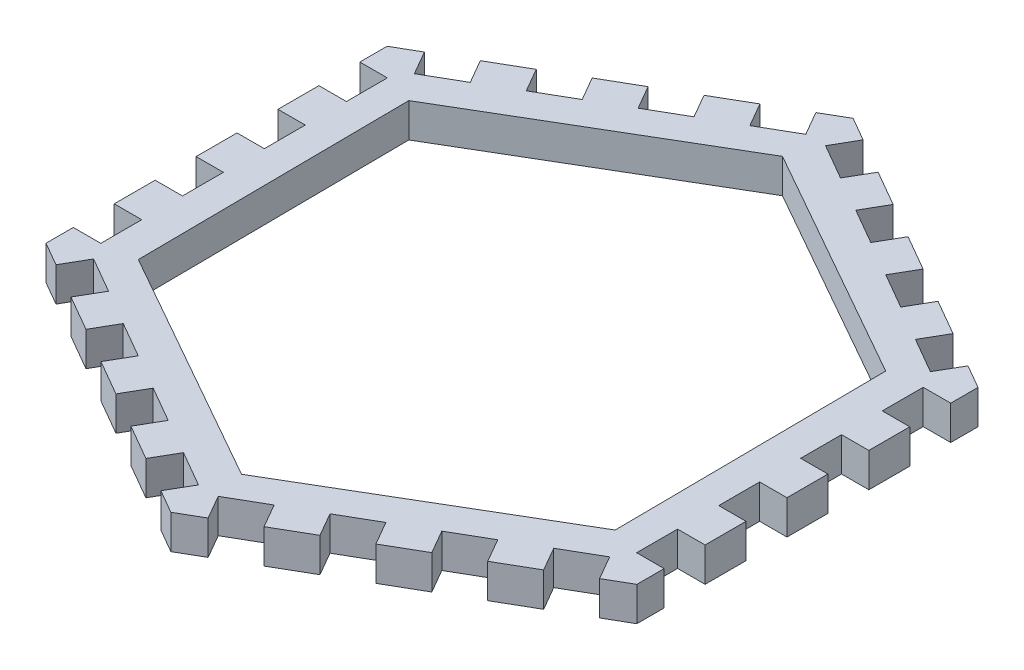
SolidWorks part; units mm, degrees
ref_plane "Front Plane" through (0, 0, 0) normal (0, 0, 1) x (1, 0, 0)
ref_plane "Top Plane" through (0, 0, 0) normal (0, 1, 0) x (1, 0, 0)
ref_plane "Right Plane" through (0, 0, 0) normal (1, 0, 0) x (0, 0, -1)
sketch "Sketch1" plane through (0, 0, 0) normal (0, 1, 0) x (1, 0, 0)
  line L0 (-13.7482, 23.8125) -> (-10.2854, 17.8149) construction
  line L1 (27.4963, 15.875) -> (0, 31.75) construction
  line L2 (0, 31.75) -> (-27.4963, 15.875) construction
  line L3 (-27.4963, 15.875) -> (-27.4963, -15.875) construction
  line L4 (-27.4963, -15.875) -> (0, -31.75) construction
  line L5 (0, -31.75) -> (27.4963, -15.875) construction
  line L6 (27.4963, -15.875) -> (27.4963, 15.875) construction
  line L7 (21.8831, 12.8954) -> (-0.2262, 25.399)
  line L8 (-0.2262, 25.399) -> (-22.1093, 12.5036)
  line L9 (-22.1093, 12.5036) -> (-21.8831, -12.8954)
  line L10 (-21.8831, -12.8954) -> (0.2262, -25.399)
  line L11 (0.2262, -25.399) -> (22.1093, -12.5036)
  line L12 (22.1093, -12.5036) -> (21.8831, 12.8954)
  line L13 (-27.4963, 15.875) -> (-25.2966, 17.145)
  line L14 (-25.2966, 17.145) -> (-24.0164, 14.9276)
  line L15 (-24.0164, 14.9276) -> (-20.7168, 16.8326)
  line L16 (-20.7168, 16.8326) -> (-21.997, 19.05)
  line L17 (-21.997, 19.05) -> (-18.6975, 20.955)
  line L18 (-18.6975, 20.955) -> (-17.4275, 18.7553)
  line L19 (-17.4275, 18.7553) -> (-14.1279, 20.6603)
  line L20 (-14.1279, 20.6603) -> (-15.3979, 22.86)
  line L21 (-15.3979, 22.86) -> (-12.0984, 24.765)
  line L22 (-10.8284, 22.5653) -> (-12.0984, 24.765)
  line L23 (-7.5288, 24.4703) -> (-10.8284, 22.5653)
  line L24 (-8.7988, 26.67) -> (-7.5288, 24.4703)
  line L25 (-5.4993, 28.575) -> (-8.7988, 26.67)
  line L26 (-4.2191, 26.3576) -> (-5.4993, 28.575)
  line L27 (-0.9195, 28.2626) -> (-4.2191, 26.3576)
  line L28 (-2.1997, 30.48) -> (-0.9195, 28.2626)
  line L29 (0, 31.75) -> (-2.1997, 30.48)
  line L30 (0, 31.75) -> (2.1997, 30.48)
  line L31 (2.1997, 30.48) -> (0.9195, 28.2626)
  line L32 (0.9195, 28.2626) -> (4.2191, 26.3576)
  line L33 (4.2191, 26.3576) -> (5.4993, 28.575)
  line L34 (5.4993, 28.575) -> (8.7988, 26.67)
  line L35 (8.7988, 26.67) -> (7.5288, 24.4703)
  line L36 (7.5288, 24.4703) -> (10.8284, 22.5653)
  line L37 (10.8284, 22.5653) -> (12.0984, 24.765)
  line L38 (12.0984, 24.765) -> (15.3979, 22.86)
  line L39 (14.1279, 20.6603) -> (15.3979, 22.86)
  line L40 (17.4275, 18.7553) -> (14.1279, 20.6603)
  line L41 (18.6975, 20.955) -> (17.4275, 18.7553)
  line L42 (21.997, 19.05) -> (18.6975, 20.955)
  line L43 (20.7168, 16.8326) -> (21.997, 19.05)
  line L44 (24.0164, 14.9276) -> (20.7168, 16.8326)
  line L45 (25.2966, 17.145) -> (24.0164, 14.9276)
  line L46 (27.4963, 15.875) -> (25.2966, 17.145)
  line L47 (27.4963, 15.875) -> (27.4963, 13.335)
  line L48 (27.4963, 13.335) -> (24.9359, 13.335)
  line L49 (24.9359, 13.335) -> (24.9359, 9.525)
  line L50 (24.9359, 9.525) -> (27.4963, 9.525)
  line L51 (27.4963, 9.525) -> (27.4963, 5.715)
  line L52 (27.4963, 5.715) -> (24.9563, 5.715)
  line L53 (24.9563, 5.715) -> (24.9563, 1.905)
  line L54 (24.9563, 1.905) -> (27.4963, 1.905)
  line L55 (27.4963, 1.905) -> (27.4963, -1.905)
  line L56 (24.9563, -1.905) -> (27.4963, -1.905)
  line L57 (24.9563, -5.715) -> (24.9563, -1.905)
  line L58 (27.4963, -5.715) -> (24.9563, -5.715)
  line L59 (27.4963, -9.525) -> (27.4963, -5.715)
  line L60 (24.9359, -9.525) -> (27.4963, -9.525)
  line L61 (24.9359, -13.335) -> (24.9359, -9.525)
  line L62 (27.4963, -13.335) -> (24.9359, -13.335)
  line L63 (27.4963, -15.875) -> (27.4963, -13.335)
  line L64 (27.4963, -15.875) -> (25.2966, -17.145)
  line L65 (25.2966, -17.145) -> (24.0164, -14.9276)
  line L66 (24.0164, -14.9276) -> (20.7168, -16.8326)
  line L67 (20.7168, -16.8326) -> (21.997, -19.05)
  line L68 (21.997, -19.05) -> (18.6975, -20.955)
  line L69 (18.6975, -20.955) -> (17.4275, -18.7553)
  line L70 (17.4275, -18.7553) -> (14.1279, -20.6603)
  line L71 (14.1279, -20.6603) -> (15.3979, -22.86)
  line L72 (15.3979, -22.86) -> (12.0984, -24.765)
  line L73 (10.8284, -22.5653) -> (12.0984, -24.765)
  line L74 (7.5288, -24.4703) -> (10.8284, -22.5653)
  line L75 (8.7988, -26.67) -> (7.5288, -24.4703)
  line L76 (5.4993, -28.575) -> (8.7988, -26.67)
  line L77 (4.2191, -26.3576) -> (5.4993, -28.575)
  line L78 (0.9195, -28.2626) -> (4.2191, -26.3576)
  line L79 (2.1997, -30.48) -> (0.9195, -28.2626)
  line L80 (0, -31.75) -> (2.1997, -30.48)
  line L81 (0, -31.75) -> (-2.1997, -30.48)
  line L82 (-2.1997, -30.48) -> (-0.9195, -28.2626)
  line L83 (-0.9195, -28.2626) -> (-4.2191, -26.3576)
  line L84 (-4.2191, -26.3576) -> (-5.4993, -28.575)
  line L85 (-5.4993, -28.575) -> (-8.7988, -26.67)
  line L86 (-8.7988, -26.67) -> (-7.5288, -24.4703)
  line L87 (-7.5288, -24.4703) -> (-10.8284, -22.5653)
  line L88 (-10.8284, -22.5653) -> (-12.0984, -24.765)
  line L89 (-12.0984, -24.765) -> (-15.3979, -22.86)
  line L90 (-14.1279, -20.6603) -> (-15.3979, -22.86)
  line L91 (-17.4275, -18.7553) -> (-14.1279, -20.6603)
  line L92 (-18.6975, -20.955) -> (-17.4275, -18.7553)
  line L93 (-21.997, -19.05) -> (-18.6975, -20.955)
  line L94 (-20.7168, -16.8326) -> (-21.997, -19.05)
  line L95 (-24.0164, -14.9276) -> (-20.7168, -16.8326)
  line L96 (-25.2966, -17.145) -> (-24.0164, -14.9276)
  line L97 (-27.4963, -15.875) -> (-25.2966, -17.145)
  line L98 (-27.4963, -15.875) -> (-27.4963, -13.335)
  line L99 (-27.4963, -13.335) -> (-24.9359, -13.335)
  line L100 (-24.9359, -13.335) -> (-24.9359, -9.525)
  line L101 (-24.9359, -9.525) -> (-27.4963, -9.525)
  line L102 (-27.4963, -9.525) -> (-27.4963, -5.715)
  line L103 (-27.4963, -5.715) -> (-24.9563, -5.715)
  line L104 (-24.9563, -5.715) -> (-24.9563, -1.905)
  line L105 (-24.9563, -1.905) -> (-27.4963, -1.905)
  line L106 (-27.4963, -1.905) -> (-27.4963, 1.905)
  line L107 (-24.9563, 1.905) -> (-27.4963, 1.905)
  line L108 (-24.9563, 5.715) -> (-24.9563, 1.905)
  line L109 (-27.4963, 5.715) -> (-24.9563, 5.715)
  line L110 (-27.4963, 9.525) -> (-27.4963, 5.715)
  line L111 (-24.9359, 9.525) -> (-27.4963, 9.525)
  line L112 (-24.9359, 13.335) -> (-24.9359, 9.525)
  line L113 (-27.4963, 13.335) -> (-24.9359, 13.335)
  line L114 (-27.4963, 15.875) -> (-27.4963, 13.335)
  circle A0 centre (0, 0) radius 27.4963 construction
  circle A1 centre (0, 0) radius 21.997 construction
  circle A2 centre (0, 0) radius 1.524
  point P47 (0, 0)
  point P128 (0, 0)
  dimension "D5" = 2.54
  dimension "D1" = 31.75
  dimension "D2" = 25.4
  dimension "D3" = 25.399
  dimension "D4" = 6.355
  dimension "D6" = 3.81
  dimension "D7" = 2.5604
  dimension "D8" = 3.81
  dimension "D9" = 2.54
  dimension "D10" = 3.81
  dimension "D11" = 6
extrude "Boss-Extrude1" add sketch "Sketch1" against normal blind 3.175 contours L11 L12 L7 L8 L9 L10 A2 | L5 L6 L1 L2 L3 L4 L12 L11 L10 L9 L8 L7
